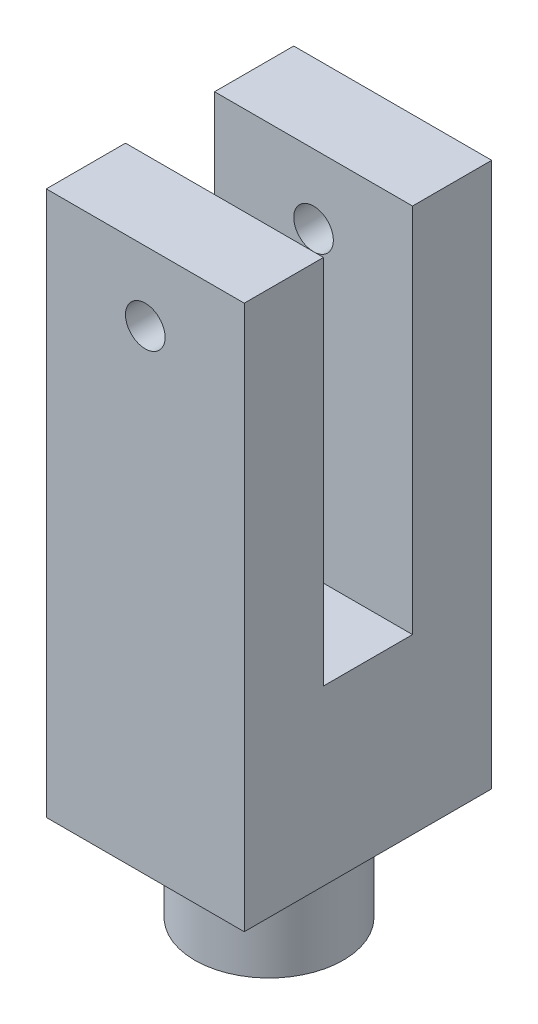
SolidWorks part; units mm, degrees
ref_plane "Front Plane" through (0, 0, 0) normal (0, 0, 1) x (1, 0, 0)
ref_plane "Top Plane" through (0, 0, 0) normal (0, 1, 0) x (1, 0, 0)
ref_plane "Right Plane" through (0, 0, 0) normal (1, 0, 0) x (0, 0, -1)
sketch "Sketch1" plane through (0, 0, 0) normal (0, 1, 0) x (1, 0, 0)
  circle A0 centre (0, 0) radius 15
extrude "Boss-Extrude1" add sketch "Sketch1" along normal blind 20
sketch "Sketch2" plane through (0, 20, 0) normal (0, 1, 0) x (1, 0, 0)
  line L1 (-20, 25) -> (20, 25)
  line L2 (-20, 25) -> (-20, -25)
  line L3 (-20, -25) -> (20, -25)
  line L4 (20, 25) -> (20, -25)
  line L5 (-20, 25) -> (20, -25) construction
  line L6 (-20, -25) -> (20, 25) construction
  point P0 (0, 0)
extrude "Boss-Extrude2" add sketch "Sketch2" along normal blind 110
sketch "Sketch3" plane through (20, 0, 0) normal (1, 0, 0) x (0, 0, -1)
  line L0 (-25, 130) -> (25, 130) construction
  line L1 (-9, 205) -> (9, 205)
  line L2 (-9, 205) -> (-9, 55)
  line L3 (-9, 55) -> (9, 55)
  line L4 (9, 205) -> (9, 55)
  line L5 (-9, 205) -> (9, 55) construction
  line L6 (-9, 55) -> (9, 205) construction
  point P0 (0, 130)
extrude "Cut-Extrude1" cut sketch "Sketch3" against normal through all
sketch "Sketch4" plane through (0, 0, -25) normal (0, 0, -1) x (-1, 0, 0)
  line L0 (-20, 20) -> (20, 20) construction
  circle A0 centre (0, 116) radius 4
  dimension "D1" = 96
extrude "Cut-Extrude2" cut sketch "Sketch4" against normal through all
